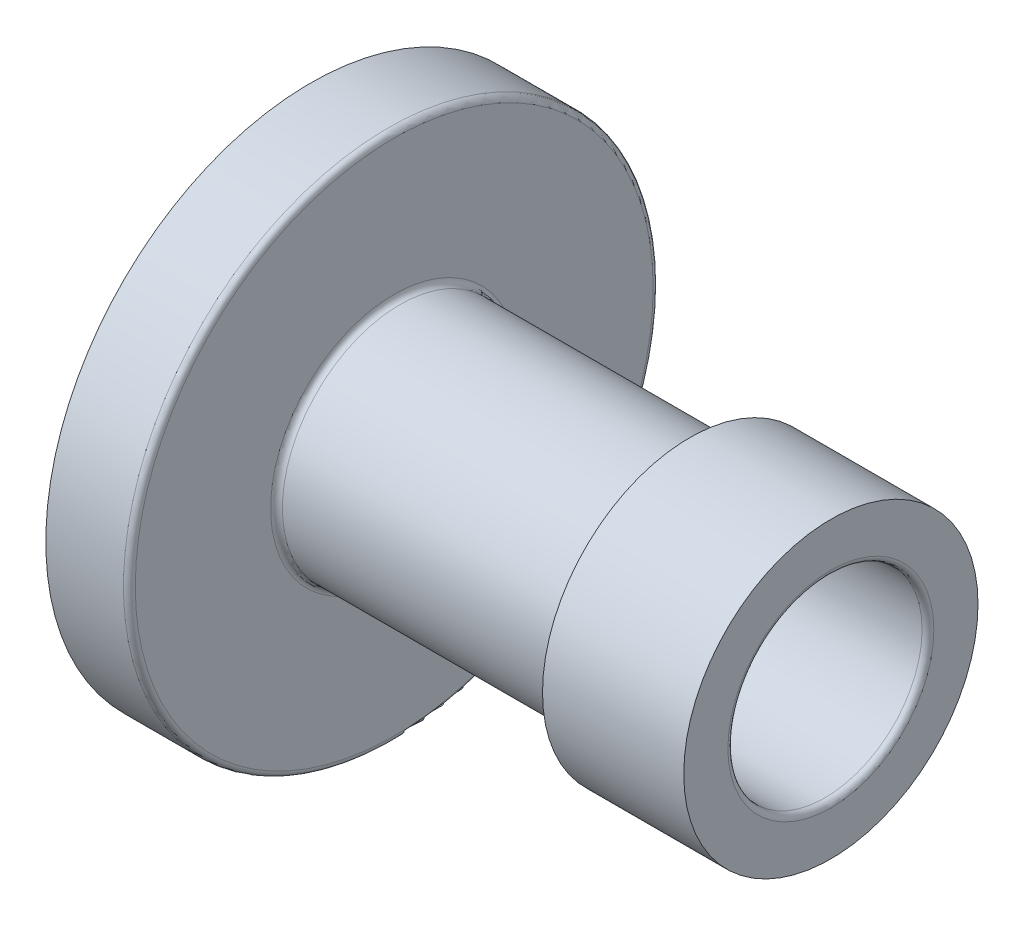
SolidWorks part; units mm, degrees
ref_plane "Front Plane" through (0, 0, 0) normal (0, 0, 1) x (1, 0, 0)
ref_plane "Top Plane" through (0, 0, 0) normal (0, 1, 0) x (1, 0, 0)
ref_plane "Right Plane" through (0, 0, 0) normal (1, 0, 0) x (0, 0, -1)
sketch "Sketch1" plane through (0, 0, 0) normal (0, 0, 1) x (1, 0, 0)
  line L0 (-44.2, 15) -> (-44.2, 60)
  line L1 (-44.2, 60) -> (-30, 60)
  line L2 (-30, 60) -> (-30, 35)
  line L3 (-30, 35) -> (20.2, 35)
  line L4 (20.2, 35) -> (20.2, 40)
  line L5 (20.2, 40) -> (44.2, 40)
  line L6 (44.2, 40) -> (44.2, 15)
  line L7 (44.2, 15) -> (-44.2, 15)
  line L8 (0, 0) -> (0, 104.1802) construction
  dimension "D1" = 15
  dimension "D2" = 88.4
  dimension "D3" = 14.2
  dimension "D4" = 24
  dimension "D5" = 45
  dimension "D6" = 25
  dimension "D7" = 20
revolve "Revolve1" add sketch "Sketch1" angle 360 about L7
hole_wizard "Hole1" positions "Sketch2" profile "Sketch3" legacy end condition through all
sketch "Sketch2" plane through (44.2, 0, 0) normal (1, 0, 0) x (0, 0, -1)
  point P0 (0, 15)
sketch "Sketch3" plane through (44.2, 15, 0) normal (0, 1, 0) x (0, 0, -1)
  line L0 (0, 0) -> (0, 88.4)
  line L1 (0, 88.4) -> (15, 88.4)
  line L2 (15, 88.4) -> (15, 0)
  line L3 (15, 0) -> (0, 0)
  line L4 (0, 110) -> (0, -10) construction
  dimension "Diameter" = 30
  dimension "Depth" = 88.4
hole_wizard "Hole2" positions "Sketch4" profile "Sketch5" legacy
sketch "Sketch4" plane through (44.2, 0, 0) normal (1, 0, 0) x (0, 0, -1)
  point P0 (0, 15)
sketch "Sketch5" plane through (44.2, 15, 0) normal (0, 1, 0) x (0, 0, -1)
  line L0 (0, 0) -> (0, 30)
  line L1 (0, 30) -> (16.5, 30)
  line L2 (16.5, 30) -> (16.5, 0)
  line L3 (16.5, 0) -> (0, 0)
  line L4 (0, 110) -> (0, -10) construction
  dimension "Diameter" = 33
  dimension "Depth" = 30
fillet "Fillet1" radius 1 3 edges at (-30, 15, -20) (-30, 15, -45) (44.2, 15, -16.5)
